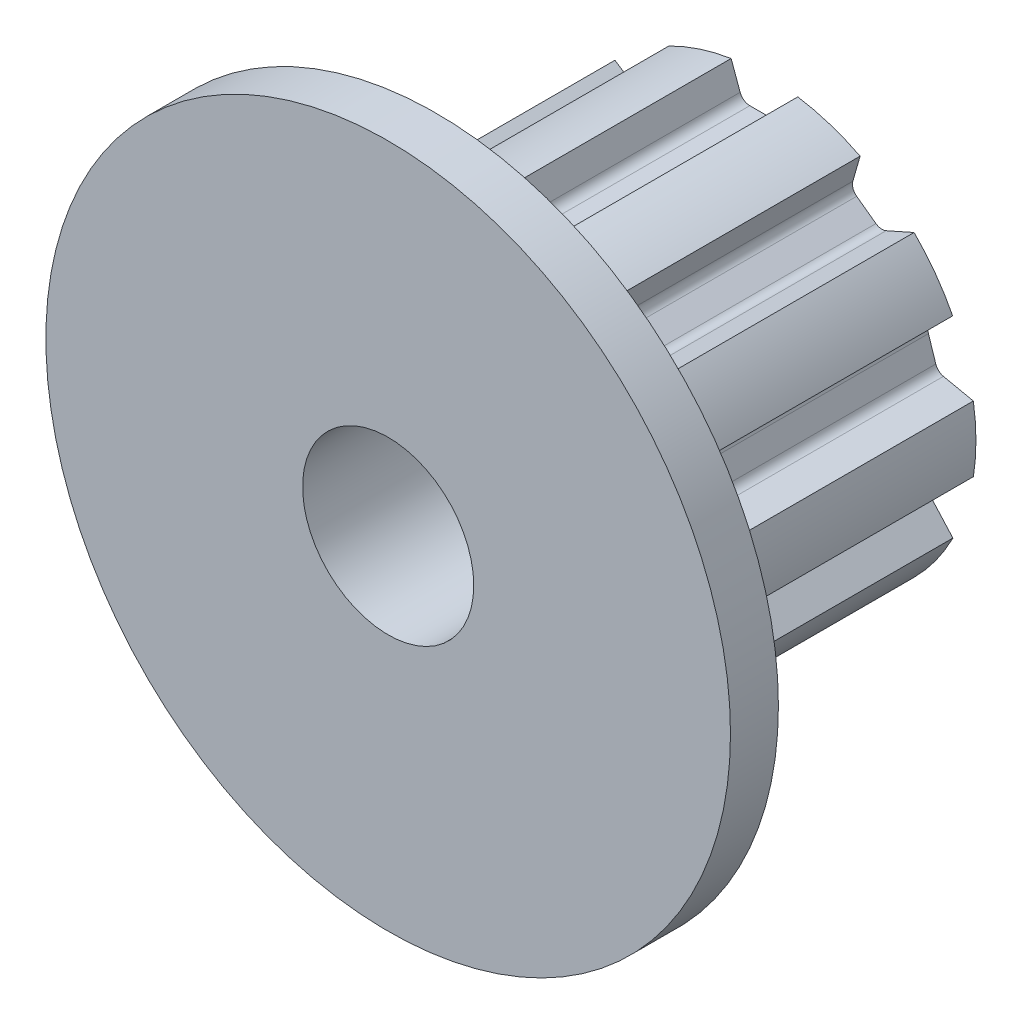
SolidWorks part; units mm, degrees
extrude "BasePulley" add sketch "Sketch1" against normal blind 12.192
sketch "Sketch1" plane through (0, 0, 0) normal (0, 0, 1) x (1, 0, 0)
  circle A0 centre (0, 0) radius 7.8359
  dimension "Outside_dia" = 15.6718
revolve "Flange" [suppressed] add sketch "Sketch2" angle 360 about L11
sketch "Sketch2" plane through (0, 0, 0) normal (1, 0, 0) x (0, 0, -1)
  line L0 (12.192, 7.8359) -> (12.5026, 8.8519)
  line L1 (12.5026, 8.8519) -> (13.207, 8.6365)
  line L2 (6.096, 0) -> (6.096, 66.675) construction
  line L3 (13.207, 8.6365) -> (12.9286, 7.7258)
  line L4 (12.9286, 7.7258) -> (12.9286, 0)
  line L5 (0, 7.8359) -> (-0.3106, 8.8519)
  line L6 (12.192, -7.8359) -> (12.192, 7.8359) construction
  line L7 (-0.3106, 8.8519) -> (-1.015, 8.6365)
  line L8 (-1.015, 8.6365) -> (-0.7366, 7.7258)
  line L9 (-0.7366, 7.7258) -> (-0.7366, 0)
  line L10 (12.192, 7.8359) -> (0, 7.8359)
  line L11 (0, 0) -> (38.2092, 0) construction
  line L12 (12.192, 0) -> (0, 0) construction
  line L13 (-0.7366, 0) -> (12.9286, 0)
  dimension "D1" = 6.096
  dimension "Flange_ang" = 17
  dimension "D3" = 0.7366
  dimension "D2" = 7.8359
  dimension "Flange_ht" = 1.016
ref_plane "Plane1" through (0, 0, 0) normal (0, 0, 1) x (1, 0, 0)
ref_plane "Plane2" through (0, 0, 0) normal (0, 1, 0) x (1, 0, 0)
ref_plane "Plane3" through (0, 0, 0) normal (1, 0, 0) x (0, 0, -1)
sketch "Clipboard" plane through (0, 0, 0) normal (0, 0, 1) x (1, 0, 0)
  line L0 (0, 0) -> (6.604, 0)
  line L1 (0, 0) -> (13.7578, 2.4259)
  line L2 (0, 0) -> (13.7578, -2.4259)
ref_plane "Plane4" through (0, 0, -6.096) normal (0, 0, 1) x (1, 0, 0)
sketch "Sketch3" plane through (0, 0, -6.096) normal (0, 0, 1) x (1, 0, 0)
  line L0 (-1.2827, 7.8359) -> (-1.2827, 33.2359)
  line L1 (1.2827, 7.8359) -> (1.2827, 33.2359)
  line L2 (0, 0) -> (0, 7.8359) construction
  line L3 (-1.2827, 7.8359) -> (1.2827, 7.8359) construction
  line L4 (-0.5537, 6.5659) -> (0.3295, 6.5659)
  line L5 (1.2827, 7.8359) -> (0.6595, 6.7564)
  line L6 (-1.2827, 7.8359) -> (-0.9117, 6.8166)
  line L7 (1.2827, 33.2359) -> (-1.2827, 33.2359)
  arc A0 (0.3295, 6.5659) -> (0.6595, 6.7564) centre (0.3295, 6.9469) ccw
  arc A2 (-0.9117, 6.8166) -> (-0.5537, 6.5659) centre (-0.5537, 6.9469) ccw
  dimension "Grv_rad_bot" = 0.381
  dimension "Grv_ang" = 50
  dimension "D3" = 20
  dimension "Grv_width" = 2.5654
  dimension "D4" = 25.4
  dimension "D1" = 7.8359
  dimension "Grv_depth" = 1.27
extrude "Groove" cut sketch "Sketch3" against normal mid plane 12.192
pattern_circular "Grooves" count 10 every 36 about axis through (0, 0, -12.192) along (0, 0, 1) of "Groove"
sketch "Sketch4" plane through (0, 0, 0) normal (1, 0, 0) x (0, 0, -1)
  line L0 (0, 0) -> (47.6781, 0) construction
  line L1 (12.192, 0) -> (0, 0) construction
  line L2 (0, 0) -> (-1.778, 0)
  line L3 (-1.778, 0) -> (-1.778, 12.7)
  line L4 (-1.778, 12.7) -> (0, 12.7)
  line L5 (0, 12.7) -> (0, 0)
  line L6 (-1.778, -12.7) -> (0, -12.7) construction
revolve "BaseHub" add sketch "Sketch4" angle 360 about L0
sketch "BorSke" plane through (0, 0, 1.778) normal (0, 0, 1) x (1, 0, 0)
  circle A0 centre (0, 0) radius 3.175
extrude "Bore" cut sketch "BorSke" against normal through all
sketch "KeySke" plane through (0, 0, 1.778) normal (0, 0, 1) x (1, 0, 0)
  line L0 (0.127, 3.429) -> (0.127, 0)
  line L1 (0.127, 3.429) -> (-0.127, 3.429)
  line L2 (-0.127, 3.429) -> (-0.127, 0)
  line L3 (-0.127, 0) -> (0.127, 0)
  line L4 (0, 31.75) -> (0, -3.175) construction
  dimension "Width" = 12.192
extrude "Keyway" [suppressed] cut sketch "KeySke" against normal through all
pattern_circular "Keyway2" [suppressed] count 2 every 90
equation "\"D1@Plane4\" = \"Width@BasePulley\" / 2"
equation "\"D1@Groove\" = \"Width@BasePulley\""
equation "\"D1@Sketch3\" = \"Outside_dia@Sketch1\" / 2"
equation "\"D1@Sketch2\" = \"Width@BasePulley\" / 2"
equation "\"D2@Sketch2\" = \"Outside_dia@Sketch1\" / 2"
equation "\"D3@Sketch2\" = \"Flange_thickness@Sketch2\""
equation "\"Num_grvs@Clipboard\" = int( \"Num_grvs@Clipboard\" )"
equation "\"Show_grvs@Clipboard\" = int( \"Show_grvs@Clipboard\" )"
equation "\"Show_grvs@Clipboard\" = ((sgn( \"Show_grvs@Clipboard\" - \"Num_grvs@Clipboard\" )-1)*( \"Show_grvs@Clipboard\" - \"Num_grvs@Clipboard\" ))/-2+ \"Num_grvs@Clipboard\""
equation "\"Show_grvs@Clipboard\" = ((sgn( \"Show_grvs@Clipboard\" - 1.0)+1)*( \"Show_grvs@Clipboard\" - 1.0))/2 +1.0"
equation "\"Angle@Grooves\" = 360.0 / \"Num_grvs@Clipboard\""
equation "\"Num_grvs@Grooves\" =  \"Show_grvs@Clipboard\""
equation "\"Offset@KeySke\" = \"T_dim@Clipboard\" - \"Diameter@BorSke\" / 2.0"
equation "\"OAL@Clipboard\" = \"Overall_len@Clipboard\""
equation "\"Hub_depth@Sketch4\" = \"OAL@Clipboard\" - \"Width@BasePulley\""
